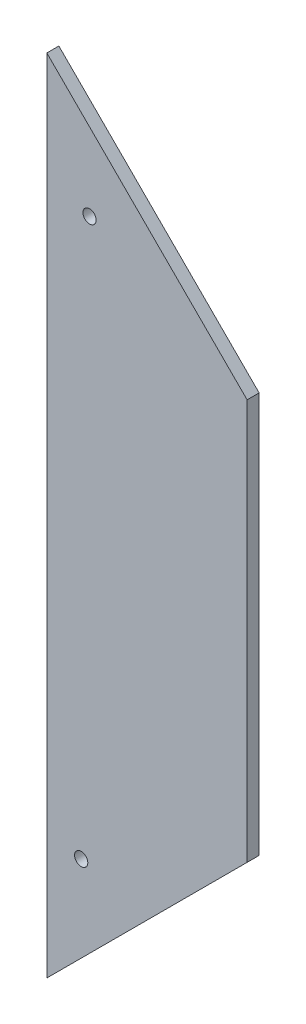
SolidWorks part; units mm, degrees
material "Сосна"
ref_plane "Спереди" through (0, 0, 0) normal (0, 0, 1) x (1, 0, 0)
ref_plane "Сверху" through (0, 0, 0) normal (0, 1, 0) x (1, 0, 0)
ref_plane "Справа" through (0, 0, 0) normal (1, 0, 0) x (0, 0, -1)
sketch "Эскиз1" plane through (0, 0, 0) normal (0, 0, 1) x (1, 0, 0)
  line L0 (0, 0) -> (0, 200)
  line L1 (0, 0) -> (50, 50)
  line L2 (50, 50) -> (50, 150)
  line L3 (50, 150) -> (0, 200)
  dimension "D1" = 200
  dimension "D2" = 50
  dimension "D3" = 45
  dimension "D4" = 45
extrude "Бобышка-Вытянуть1" add sketch "Эскиз1" along normal blind 3
sketch "Эскиз3" plane through (0, 0, 0) normal (-1, 0, 0) x (0, 0, 1)
  line L0 (1.5, 200) -> (1.5, -113.6649) construction
  line L1 (3, 200) -> (0, 200) construction
sketch "Эскиз4" plane through (50, 0, 0) normal (1, 0, 0) x (0, 0, -1)
  line L0 (-1.5, 150) -> (-1.5, -28.0184) construction
  line L1 (-3, 150) -> (0, 150) construction
extrude "Вырез-Вытянуть1" cut sketch "Эскиз5" against normal blind 8 contours L4 A0 | A0 L4 | A1
sketch "Эскиз5" plane through (-305.9612, -184.2045, -1.5) normal (0, 0, -1) x (-0.9999, 0.0149, 0)
  line L0 (-300.2088, 388.7158) -> (-304.8774, 75.0857) construction
  line L2 (-317.5586, 363.9713) -> (-305.06, 363.7853)
  line L3 (-317.7074, 353.9725) -> (-305.2088, 353.7864)
  line L4 (-311.3093, 363.8783) -> (-311.3093, 353.8772) construction
  circle A0 centre (-311.3093, 358.8778) radius 1.65
  circle A1 centre (-311.3093, 218.8778) radius 1.65
  dimension "D1" = 10.6552
  dimension "D2" = 29.8381
  dimension "D3" = 2
